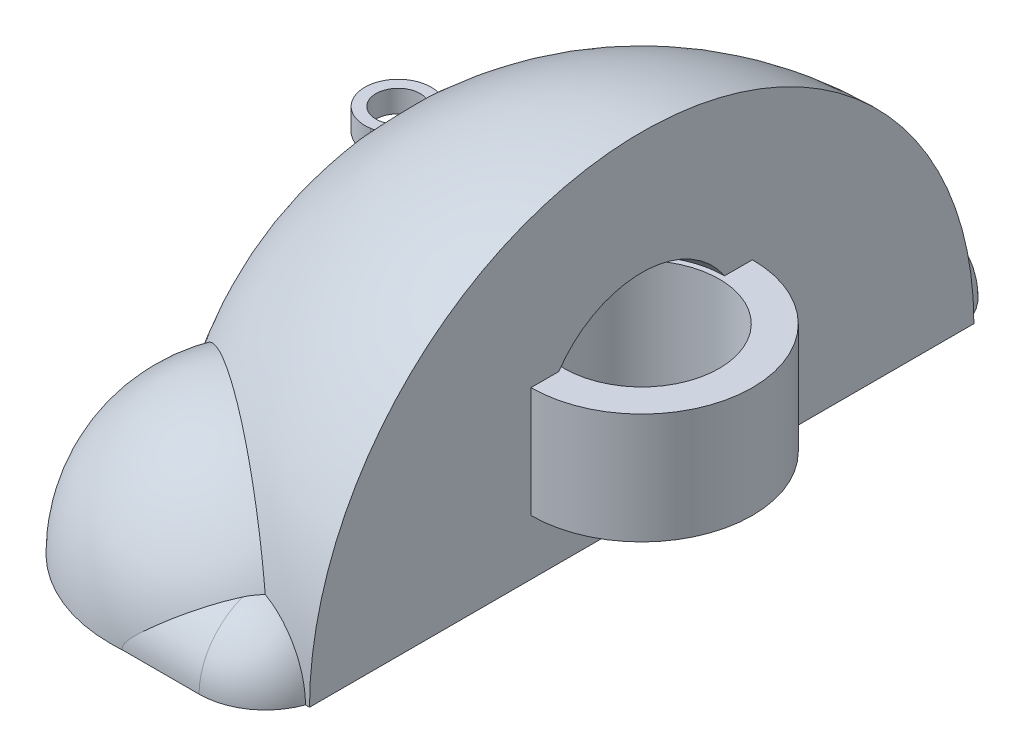
SolidWorks part; units mm, degrees
ref_plane "Alzado" through (0, 0, 0) normal (0, 0, 1) x (1, 0, 0)
ref_plane "Planta" through (0, 0, 0) normal (0, 1, 0) x (1, 0, 0)
ref_plane "Vista lateral" through (0, 0, 0) normal (1, 0, 0) x (0, 0, -1)
sketch "Croquis2" plane through (0, 0, 0) normal (0, 1, 0) x (1, 0, 0)
  line L0 (0, 15) -> (0, -15)
  arc A0 (0, 15) -> (0, -15) centre (0, 0) ccw
  dimension "D1" = 30
revolve "Revolución1" add sketch "Croquis2" angle 90 about L0
sketch "Croquis21" plane through (0, 0, 0) normal (0, 1, 0) x (1, 0, 0)
  line L0 (-7, -3) -> (-7, -17)
  arc A0 (-7, -3) -> (-7, -17) centre (-7, -10) ccw
  dimension "D1" = 14
  dimension "D2" = 7
  dimension "D3" = 5
revolve "Revolución16" add sketch "Croquis21" angle 180 about L0
sketch "Croquis22" plane through (0, 0, 0) normal (0, 1, 0) x (1, 0, 0)
  line L10 (-8.4972, -13.9809) -> (-3.0069, -13.9809) construction
  line L11 (-7.0136, -16.9809) -> (-3.0069, -16.9809)
  line L14 (-0.0069, -13.9809) -> (-8.4972, -13.9809)
  line L16 (-8.4972, -13.9809) -> (-8.4729, -15.1338)
  arc A5 (-3.0069, -16.9809) -> (-0.0069, -13.9809) centre (-3.0069, -13.9809) ccw
  arc A6 (-7.0136, -16.9809) -> (-8.4729, -15.1338) centre (-7.0136, -15.4809) cw
  dimension "D1" = 3
sketch "Croquis23" plane through (0, 0, 0) normal (0, 1, 0) x (1, 0, 0)
  line L0 (-7, 17) -> (-7, 3)
  line L1 (0, -15) -> (0, 15) construction
  arc A0 (-7, 17) -> (-7, 3) centre (-7, 10) ccw
  dimension "D1" = 7
  dimension "D2" = 5
revolve "Revolución20" add sketch "Croquis23" angle 180 about L0
sketch "Croquis25" plane through (0, 0, 0) normal (0, 1, 0) x (1, 0, 0)
  line L4 (-8.5501, 13.9966) -> (-3.0488, 13.9966) construction
  line L5 (-7.0251, 10.9966) -> (-3.0488, 10.9966)
  line L6 (-0.0488, 13.9966) -> (-8.5501, 13.9966)
  line L7 (-8.5501, 13.9966) -> (-8.5148, 12.3214)
  arc A1 (-3.0488, 10.9966) -> (-0.0488, 13.9966) centre (-3.0488, 13.9966) ccw
  arc A2 (-7.0251, 10.9966) -> (-8.5148, 12.3214) centre (-7.0251, 12.4966) cw
  dimension "D1" = 3
revolve "Revolución23" add sketch "Croquis22" angle 180 about L10
ref_plane "Plano1" through (0, 3, 0) normal (0, 1, 0) x (1, 0, 0)
ref_plane "Plano2" through (0, 5, 0) normal (0, 1, 0) x (1, 0, 0)
ref_plane "Plano3" through (0, 10, 0) normal (0, 1, 0) x (1, 0, 0)
ref_plane "Plano4" through (0, 19, 0) normal (0, 1, 0) x (1, 0, 0)
revolve "Revolución24" add sketch "Croquis25" angle 180 about L4
sketch "Croquis26" plane through (0, 0, 0) normal (1, 0, 0) x (0, 0, -1)
  line L0 (-4.5, 5) -> (4.5, 5)
  arc A0 (-4.5, 5) -> (4.5, 5) centre (0, 5) ccw
  dimension "D1" = 9
  dimension "D2" = 5
revolve "Cortar-Revolución1" cut sketch "Croquis26" angle 360 about L0
sketch "Croquis29" plane through (0, 5, 0) normal (0, 1, 0) x (1, 0, 0)
  line L0 (0, -15) -> (0, 15) construction
  circle A0 centre (0, 0) radius 5
  circle A1 centre (0, 0) radius 3.5
  dimension "D1" = 10
  dimension "D2" = 7
  dimension "D3" = 0
  dimension "D4" = 0
extrude "Saliente-Extruir1" add sketch "Croquis29" along normal blind 2.5 and the other way blind 2.5
ref_plane "Plano5" through (-11, 0, 0) normal (1, 0, 0) x (0, 0, -1)
sketch "Croquis32" plane through (-11, 0, 0) normal (1, 0, 0) x (0, 0, -1)
  line L0 (1.5448, 9.9803) -> (-1.5448, 9.9803)
  arc A0 (1.5448, 9.9803) -> (-1.5448, 9.9803) centre (0, 9.9803) ccw
revolve "Cortar-Revolución2" cut sketch "Croquis32" angle 360 about L0
sketch "Croquis31" plane through (0, 10, 0) normal (0, 1, 0) x (1, 0, 0)
  line L0 (-11, -8.4318) -> (-11, 8.4318) construction
  circle A0 centre (-11, 0) radius 1.5
  circle A1 centre (-11, 0) radius 1
  point P3 (-11, 0)
  dimension "D1" = 2
  dimension "D2" = 3
extrude "Saliente-Extruir2" add sketch "Croquis31" along normal blind 0.5 and the other way blind 0.5
